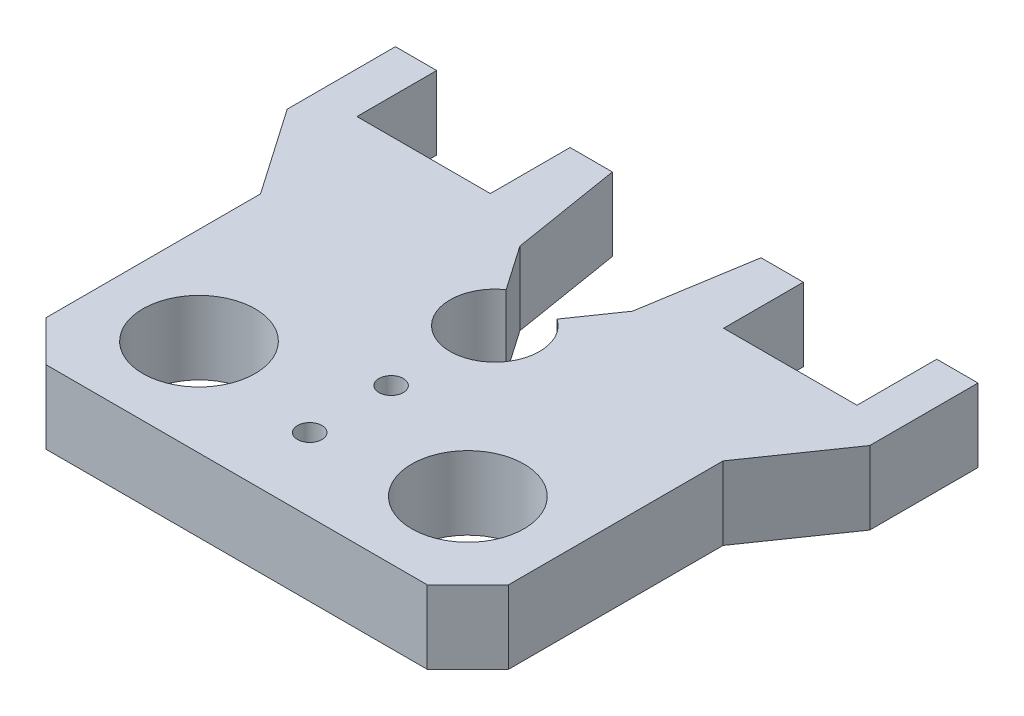
SolidWorks part; units mm, degrees
ref_plane "Front Plane" through (0, 0, 0) normal (0, 0, 1) x (1, 0, 0)
ref_plane "Top Plane" through (0, 0, 0) normal (0, 1, 0) x (1, 0, 0)
ref_plane "Right Plane" through (0, 0, 0) normal (1, 0, 0) x (0, 0, -1)
sketch "Sketch1" plane through (0, 0, 0) normal (0, 1, 0) x (1, 0, 0)
  line L0 (-11.6527, -50.5705) -> (4.8468, -50.5705)
  line L1 (14.8971, -56.0479) -> (18.6878, -50.5705)
  line L3 (8.6374, -56.0479) -> (4.8468, -50.5705)
  line L4 (18.6878, -50.5705) -> (35.1873, -50.5705)
  line L36 (11.7673, -80.4005) -> (11.7673, -92.3005) construction
  line L38 (-4.7527, -80.4005) -> (28.2873, -80.4005) construction
  line L39 (11.7673, -83.3155) -> (11.7673, -80.4005) construction
  line L40 (35.1873, -92.3005) -> (40.1873, -87.3005)
  line L41 (-11.6527, -92.3005) -> (35.1873, -92.3005)
  line L42 (-16.6527, -87.3005) -> (-16.6527, -55.5705)
  line L44 (40.1873, -87.3005) -> (40.1873, -55.5705)
  line L45 (-16.6527, -71.4355) -> (40.1873, -71.4355) construction
  line L46 (-11.6527, -92.3005) -> (-16.6527, -87.3005)
  line L47 (35.1873, -50.5705) -> (40.1873, -55.5705)
  line L48 (-11.6527, -50.5705) -> (-16.6527, -55.5705)
  line L50 (40.1873, -87.3005) -> (40.2521, -86.952) construction
  arc A0 (8.6374, -56.0479) -> (14.8971, -56.0479) centre (11.7673, -60.5705) ccw
  circle A5 centre (11.7673, -73.3155) radius 1.5
  circle A6 centre (11.7673, -83.3155) radius 1.5
  circle A11 centre (-4.7527, -80.4005) radius 6.9
  circle A12 centre (28.2873, -80.4005) radius 6.9
  dimension "D16" = 13.8
  dimension "D17" = 13.8
  dimension "D18" = 2.915
  dimension "D19" = 33.04
  dimension "D3" = 11
  dimension "D20" = 11.9
  dimension "D22" = 56.84
extrude "Boss-Extrude1" add sketch "Sketch1" along normal blind 9
sketch "Sketch2" plane through (0, 9, 0) normal (0, 1, 0) x (1, 0, 0)
  line L0 (26.0998, -36.9881) -> (20.8998, -36.9881)
  line L1 (20.8998, -36.9881) -> (18.6878, -50.5705)
  line L2 (26.0998, -36.9881) -> (26.0998, -46.7881)
  line L3 (40.1873, -55.5705) -> (40.1873, -60.9363)
  line L4 (26.0998, -46.7881) -> (42.4904, -46.7881)
  line L5 (40.1873, -55.5705) -> (35.1873, -50.5705)
  line L6 (35.1873, -50.5705) -> (18.6878, -50.5705)
  line L7 (42.4904, -46.7881) -> (42.4904, -36.9881)
  line L8 (11.7673, -66.0705) -> (11.7673, -27.5764) construction
  line L9 (47.5604, -36.9881) -> (47.5604, -50.2881)
  line L10 (47.5604, -50.2881) -> (40.1873, -60.9363)
  line L11 (40.1873, -87.3005) -> (40.1873, -55.5705) construction
  line L12 (-18.9559, -36.9881) -> (-24.0259, -36.9881)
  line L13 (-24.0259, -50.2881) -> (-16.6527, -60.9363)
  line L14 (-24.0259, -36.9881) -> (-24.0259, -50.2881)
  line L15 (-18.9559, -46.7881) -> (-18.9559, -36.9881)
  line L16 (-11.6527, -50.5705) -> (4.8468, -50.5705)
  line L17 (-16.6527, -55.5705) -> (-11.6527, -50.5705)
  line L18 (42.4904, -36.9881) -> (47.5604, -36.9881)
  line L19 (-2.5653, -46.7881) -> (-18.9559, -46.7881)
  line L20 (-16.6527, -55.5705) -> (-16.6527, -60.9363)
  line L21 (-2.5653, -36.9881) -> (-2.5653, -46.7881)
  line L22 (2.6347, -36.9881) -> (4.8468, -50.5705)
  line L23 (-2.5653, -36.9881) -> (2.6347, -36.9881)
  arc A0 (8.6374, -56.0479) -> (14.8971, -56.0479) centre (11.7673, -60.5705) ccw construction
  dimension "D2" = 5.2
  dimension "D3" = 9.8
  dimension "D4" = 5.07
  dimension "D6" = 79.7
  dimension "D7" = 13.3
  dimension "D8" = 13.5824
  dimension "D9" = 80.75
  dimension "D10" = 90
extrude "Boss-Extrude2" add sketch "Sketch2" against normal up to surface (9 mm away) up to face at (-4.7527, 0, 87.3005)
